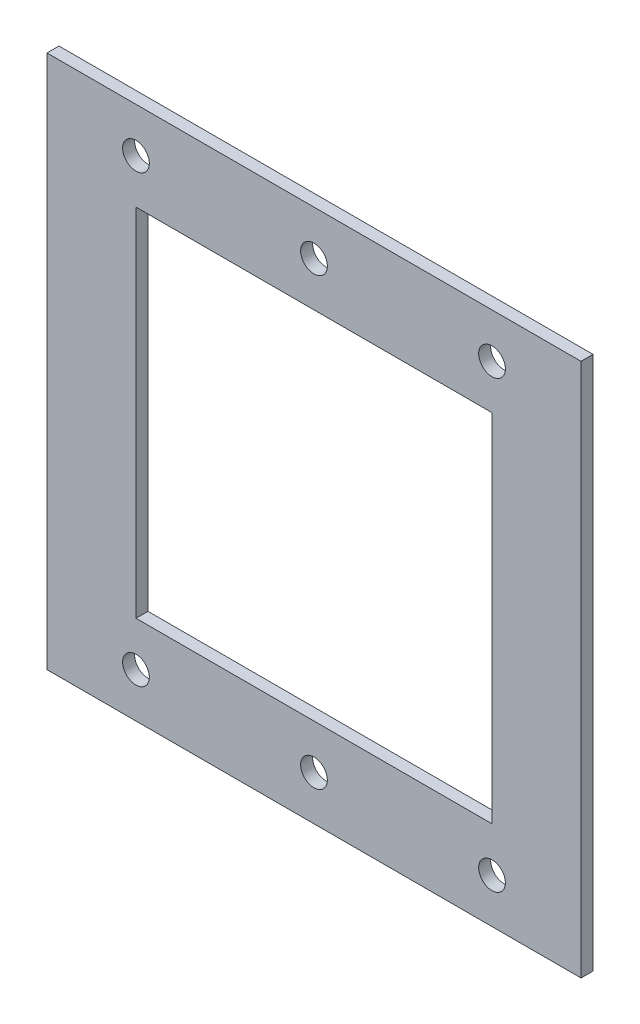
SolidWorks part; units mm, degrees
material "Acrílico (Impacto medio-alto)"
ref_plane "Alzado" through (0, 0, 0) normal (0, 0, 1) x (1, 0, 0)
ref_plane "Planta" through (0, 0, 0) normal (0, 1, 0) x (1, 0, 0)
ref_plane "Vista lateral" through (0, 0, 0) normal (1, 0, 0) x (0, 0, -1)
sketch "Croquis1" plane through (0, 0, 0) normal (0, 0, 1) x (1, 0, 0)
  line L1 (-60, -60) -> (60, -60)
  line L2 (-60, -60) -> (-60, 60)
  line L3 (-60, 60) -> (60, 60)
  line L4 (60, -60) -> (60, 60)
  line L5 (-60, -60) -> (60, 60) construction
  line L6 (-60, 60) -> (60, -60) construction
  line L7 (-40, -40) -> (40, -40)
  line L8 (-40, -40) -> (-40, 40)
  line L9 (-40, 40) -> (40, 40)
  line L10 (40, -40) -> (40, 40)
  line L11 (-40, -40) -> (40, 40) construction
  line L12 (-40, 40) -> (40, -40) construction
  circle A0 centre (-40, 50) radius 3
  circle A1 centre (0, 50) radius 3
  circle A2 centre (40, 50) radius 3
  circle A3 centre (-40, -50) radius 3
  circle A4 centre (0, -50) radius 3
  circle A5 centre (40, -50) radius 3
  point P0 (0, 0)
  point P25 (0, 0)
  dimension "D1" = 80
extrude "Saliente-Extruir1" add sketch "Croquis1" along normal blind 2.7
